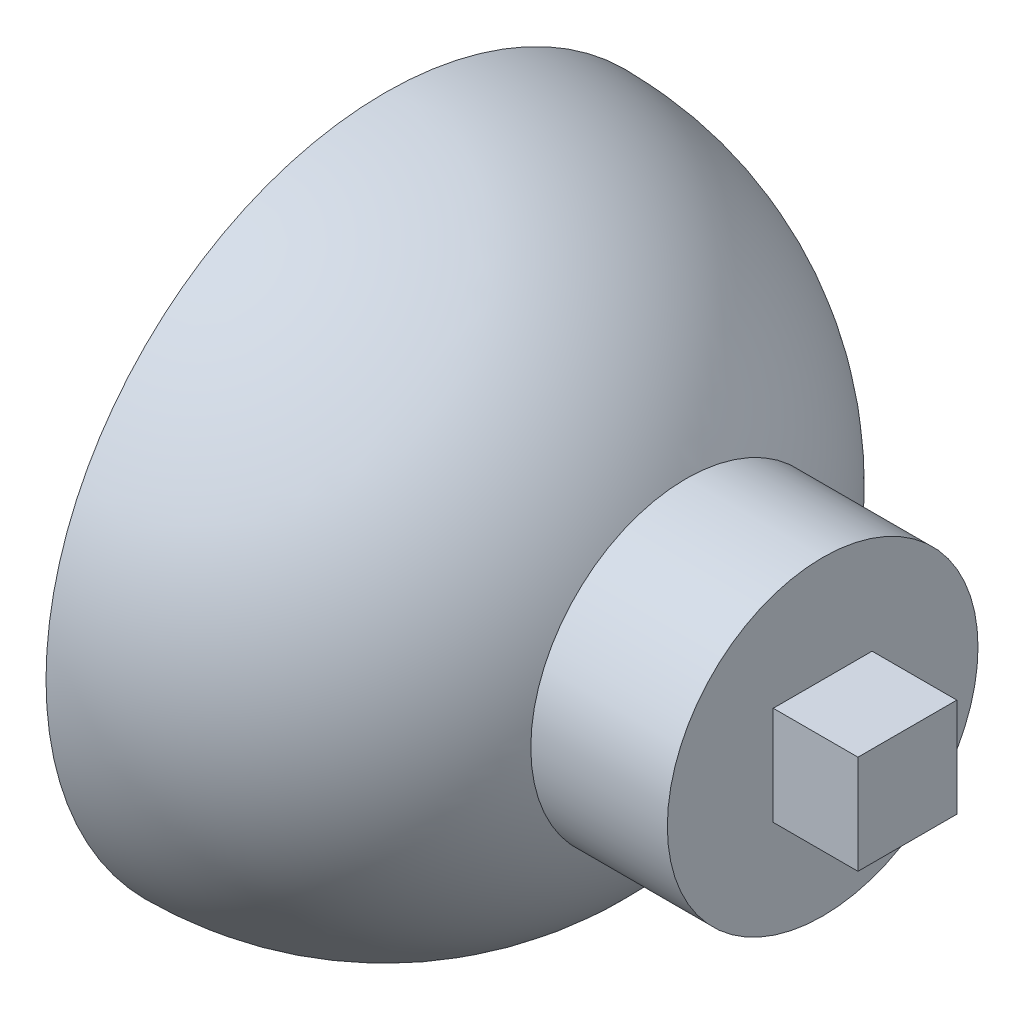
SolidWorks part; units mm, degrees
ref_plane "Front Plane" through (0, 0, 0) normal (0, 0, 1) x (1, 0, 0)
ref_plane "Top Plane" through (0, 0, 0) normal (0, 1, 0) x (1, 0, 0)
ref_plane "Right Plane" through (0, 0, 0) normal (1, 0, 0) x (0, 0, -1)
sketch "Sketch1" plane through (0, 0, 0) normal (0, 0, 1) x (1, 0, 0)
  line L0 (0, 0) -> (0, 20) construction
  line L1 (0, 0) -> (20, 0) construction
  arc A0 (20, 0) -> (0, 20) centre (0, 0) ccw
  dimension "D1" = 40
revolve "Revolve-Thin1" add sketch "Sketch1" angle 360 about L1
sketch "Sketch2" plane through (0, 0, 0) normal (-1, 0, 0) x (0, 0, 1)
  circle A0 centre (0, 0) radius 11
  dimension "D1" = 22
extrude "Boss-Extrude1" add sketch "Sketch2" against normal blind 1 and the other way up to surface from offset 30 offset against normal yes
sketch "Sketch3" plane through (0, 0, 0) normal (-1, 0, 0) x (0, 0, 1)
  point P0 (0, 0)
sketch "Sketch4" plane through (31, 0, 0) normal (1, 0, 0) x (0, 0, -1)
  line L0 (0, -11) -> (0, 11) construction
  line L2 (-3.5, -3.5) -> (3.5, -3.5)
  line L3 (-3.5, -3.5) -> (-3.5, 3.5)
  line L4 (-3.5, 3.5) -> (3.5, 3.5)
  line L5 (3.5, -3.5) -> (3.5, 3.5)
  line L6 (-3.5, -3.5) -> (3.5, 3.5) construction
  line L7 (-3.5, 3.5) -> (3.5, -3.5) construction
  circle A0 centre (0, 0) radius 11 construction
  point P0 (0, 0)
  point P7 (0, 0)
  dimension "D1" = 7
  dimension "D2" = 7
extrude "Boss-Extrude2" add sketch "Sketch4" along normal blind 6
